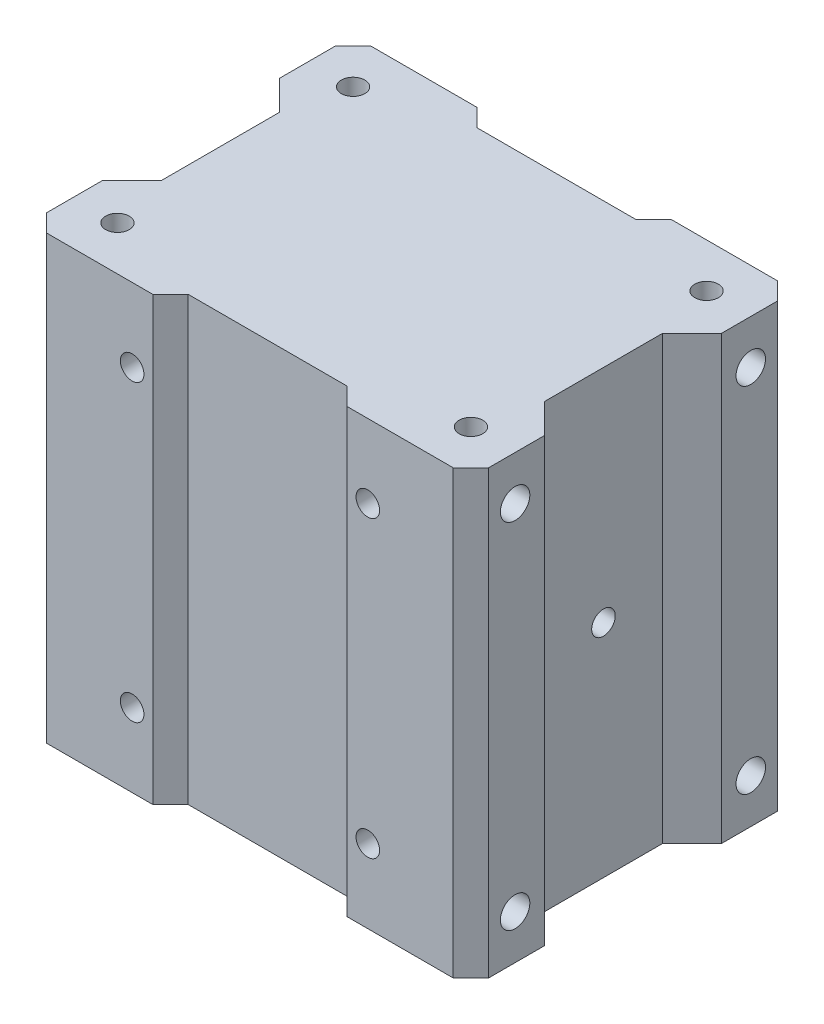
SolidWorks part; units mm, degrees
material "ABS"
ref_plane "Front Plane" through (0, 0, 0) normal (0, 0, 1) x (1, 0, 0)
ref_plane "Top Plane" through (0, 0, 0) normal (0, 1, 0) x (1, 0, 0)
ref_plane "Right Plane" through (0, 0, 0) normal (1, 0, 0) x (0, 0, -1)
sketch "Sketch1" plane through (0, 0, 0) normal (0, 1, 0) x (1, 0, 0)
  line L0 (0, -44.7868) -> (0, 44.7868) construction
  line L1 (-37.5, -27.5) -> (-16.5, -27.5)
  line L2 (-37.5, -27.5) -> (-37.5, -15)
  line L3 (-37.5, 27.5) -> (-16.5, 27.5)
  line L4 (37.5, -27.5) -> (37.5, -15)
  line L5 (-44.2539, 0) -> (44.2539, 0) construction
  line L6 (37.5, 15) -> (37.5, 27.5)
  line L7 (16.5, 27.5) -> (37.5, 27.5)
  line L8 (13.5, -24.5) -> (16.5, -27.5)
  line L9 (-16.5, 27.5) -> (-13.5, 24.5)
  line L10 (-13.5, 24.5) -> (13.5, 24.5)
  line L11 (13.5, 24.5) -> (16.5, 27.5)
  line L12 (37.5, 15) -> (32.5, 10)
  line L13 (32.5, 10) -> (32.5, -10)
  line L14 (32.5, -10) -> (37.5, -15)
  line L15 (-13.5, -24.5) -> (13.5, -24.5)
  line L16 (-16.5, -27.5) -> (-13.5, -24.5)
  line L17 (-32.5, -10) -> (-37.5, -15)
  line L18 (-32.5, 10) -> (-32.5, -10)
  line L19 (-37.5, 15) -> (-32.5, 10)
  line L20 (-37.5, 15) -> (-37.5, 27.5)
  line L21 (16.5, -27.5) -> (37.5, -27.5)
  circle A0 centre (30, 20) radius 2
  circle A1 centre (-30, 20) radius 2
  circle A2 centre (-30, -20) radius 2
  circle A3 centre (30, -20) radius 2
  point P0 (0, 0)
  point P15 (0, 24.5)
  point P16 (32.5, 0)
  dimension "D1" = 4
  dimension "D2" = 55
  dimension "D3" = 75
  dimension "D4" = 40
  dimension "D5" = 60
  dimension "D6" = 20
  dimension "D7" = 30
  dimension "D8" = 27
  dimension "D9" = 3
  dimension "D10" = 5
  dimension "D11" = 20
  dimension "D12" = 3
  dimension "D13" = 5
extrude "Boss-Extrude1" add sketch "Sketch1" along normal mid plane 75
sketch "Sketch3" plane through (0, 0, -27.5) normal (0, 0, -1) x (-1, 0, 0)
  circle A0 centre (0, 0) radius 12.75
  dimension "D1" = 25.5
extrude "Cut-Extrude1" cut sketch "Sketch3" against normal blind 35 and the other way through all
chamfer "Chamfer1" distance 3 angle 45 4 edges at (-37.5, 0, 27.5) (37.5, 0, 27.5) (37.5, 0, -27.5) (-37.5, 0, -27.5)
sketch "Sketch4" plane through (-32.5, 0, 0) normal (-1, 0, 0) x (0, 0, 1)
  circle A0 centre (0, 0) radius 2
  dimension "D1" = 4
extrude "Cut-Extrude2" cut sketch "Sketch4" against normal through all
sketch "Sketch5" plane through (-37.5, 0, 0) normal (-1, 0, 0) x (0, 0, 1)
  line L1 (55, 0) -> (-55, 0) construction
  line L2 (0, -44.2539) -> (0, 44.2539) construction
  circle A0 centre (-20, 30) radius 2.5
  circle A1 centre (-20, -30) radius 2.5
  circle A2 centre (20, -30) radius 2.5
  circle A3 centre (20, 30) radius 2.5
  dimension "D1" = 60
  dimension "D5" = 5
  dimension "D2" = 30
  dimension "D3" = 40
  dimension "D4" = 20
extrude "Cut-Extrude4" cut sketch "Sketch5" against normal through all
sketch "Sketch6" plane through (0, 0, -27.5) normal (0, 0, -1) x (-1, 0, 0)
  line L0 (0, 44.7868) -> (0, -44.7868) construction
  line L1 (55, 0) -> (-55, 0) construction
  circle A0 centre (-20, 25) radius 2
  circle A1 centre (20, 25) radius 2
  circle A2 centre (-20, -25) radius 2
  circle A3 centre (20, -25) radius 2
  dimension "D1" = 4
  dimension "D2" = 20
  dimension "D3" = 20
  dimension "D4" = 50
  dimension "D5" = 25
extrude "Cut-Extrude5" cut sketch "Sketch6" against normal through all
